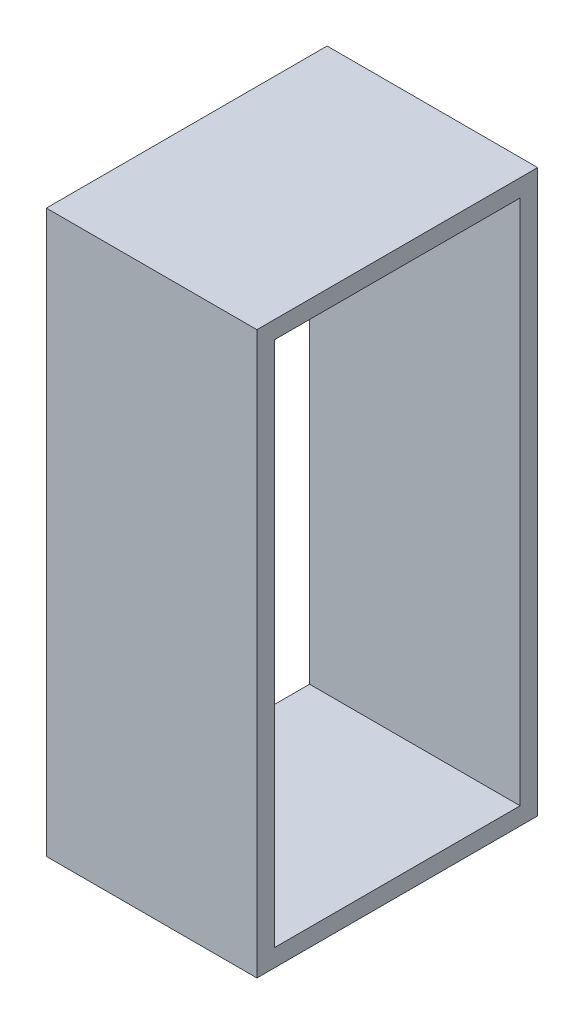
SolidWorks part; units mm, degrees
ref_plane "Front Plane" through (0, 0, 0) normal (0, 0, 1) x (1, 0, 0)
ref_plane "Top Plane" through (0, 0, 0) normal (0, 1, 0) x (1, 0, 0)
ref_plane "Right Plane" through (0, 0, 0) normal (1, 0, 0) x (0, 0, -1)
sketch "Sketch1" plane through (0, 0, 0) normal (1, 0, 0) x (0, 0, -1)
  line L1 (12.7, -25.4) -> (-12.7, -25.4)
  line L2 (12.7, -25.4) -> (12.7, 25.4)
  line L3 (12.7, 25.4) -> (-12.7, 25.4)
  line L4 (-12.7, -25.4) -> (-12.7, 25.4)
  line L5 (12.7, -25.4) -> (-12.7, 25.4) construction
  line L6 (12.7, 25.4) -> (-12.7, -25.4) construction
  line L7 (11.1125, -23.8125) -> (-11.1125, -23.8125)
  line L8 (11.1125, -23.8125) -> (11.1125, 23.8125)
  line L9 (11.1125, 23.8125) -> (-11.1125, 23.8125)
  line L10 (-11.1125, -23.8125) -> (-11.1125, 23.8125)
  line L11 (11.1125, -23.8125) -> (-11.1125, 23.8125) construction
  line L12 (11.1125, 23.8125) -> (-11.1125, -23.8125) construction
  point P0 (0, 0)
  point P6 (0, 0)
  dimension "D1" = 50.8
  dimension "D2" = 25.4
  dimension "D3" = 1.5875
  dimension "D4" = 1.5875
extrude "Boss-Extrude1" add sketch "Sketch1" along normal blind 19.05
